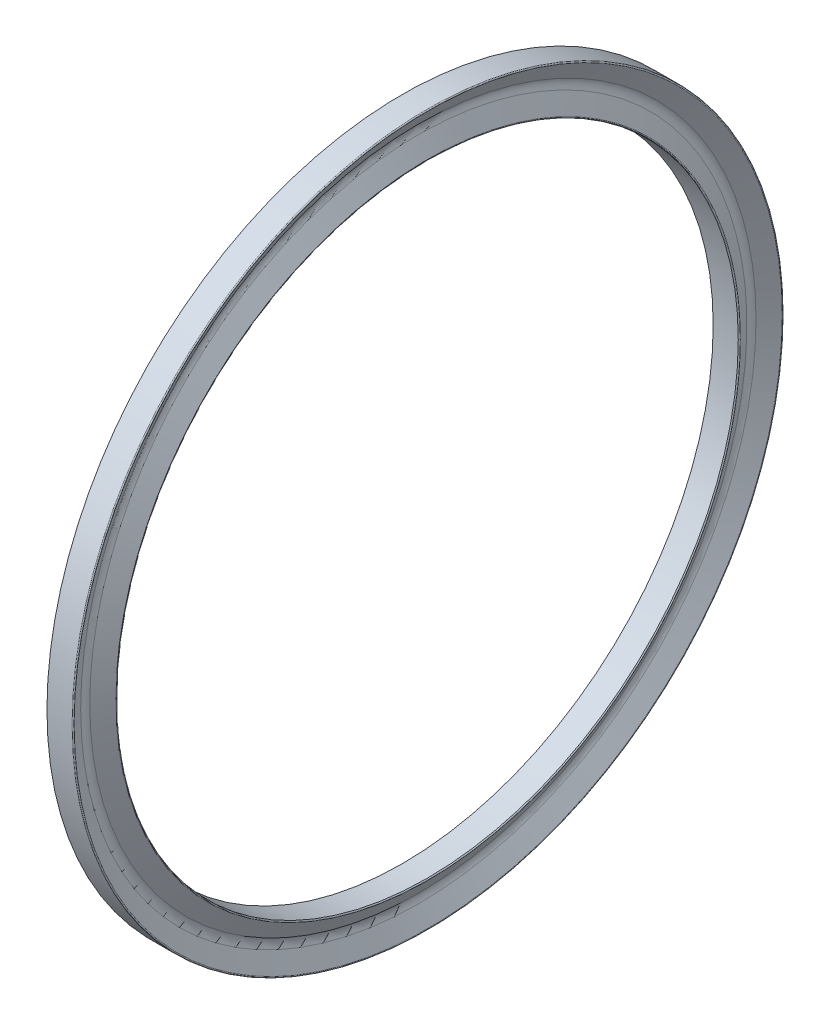
SolidWorks part; units mm, degrees
material "PP Copolymer"
ref_plane "Ön Düzlem" through (0, 0, 0) normal (0, 0, 1) x (1, 0, 0)
ref_plane "Üst Düzlem" through (0, 0, 0) normal (0, 1, 0) x (1, 0, 0)
ref_plane "Sağ Düzlem" through (0, 0, 0) normal (1, 0, 0) x (0, 0, -1)
sketch "Sketch1" plane through (0, 0, 0) normal (0, 0, 1) x (1, 0, 0)
  line L0 (-74.7573, 0) -> (81.0325, 0) construction
  line L1 (-22.4154, -40) -> (-19.592, -40)
  line L2 (-22.4154, -35) -> (-19.592, -35)
  line L3 (-22.4154, -40) -> (-22.4154, -35)
  line L4 (-19.5063, -35.1514) -> (-20.6067, -36.9855)
  line L5 (-20.6067, -38.0145) -> (-19.5063, -39.8486)
  arc A0 (-20.6067, -36.9855) -> (-20.6067, -38.0145) centre (-19.7492, -37.5) ccw
  arc A1 (-19.592, -40) -> (-19.5063, -39.8486) centre (-19.592, -39.9) ccw
  arc A2 (-19.592, -35) -> (-19.5063, -35.1514) centre (-19.592, -35.1) cw
  point P12 (-19.4154, -40)
  point P15 (-19.4154, -35)
  dimension "D5" = 1
  dimension "D6" = 0.1
  dimension "D1" = 40
  dimension "D2" = 35
  dimension "D3" = 3
  dimension "D4" = 3
revolve "Revolve1" add sketch "Sketch1" angle 360 about L0
